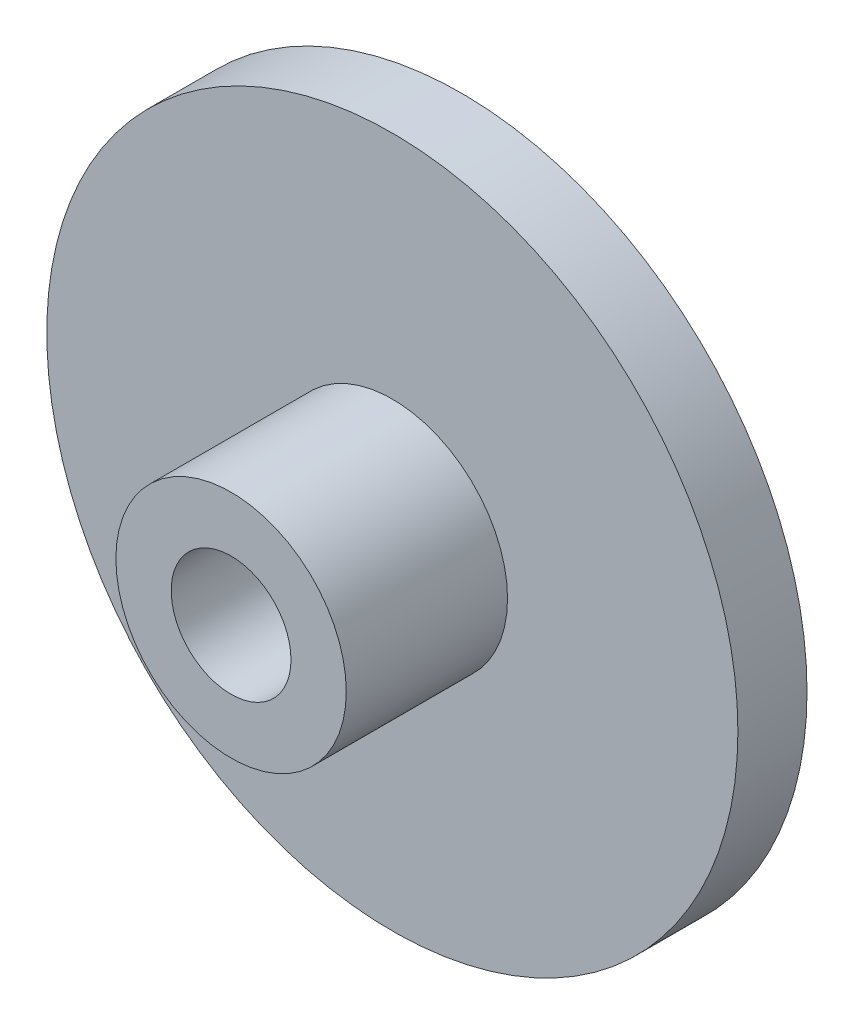
SolidWorks part; units mm, degrees
ref_plane "前视基准面" through (0, 0, 0) normal (0, 0, 1) x (1, 0, 0)
ref_plane "上视基准面" through (0, 0, 0) normal (0, 1, 0) x (1, 0, 0)
ref_plane "右视基准面" through (0, 0, 0) normal (1, 0, 0) x (0, 0, -1)
other "Configuration Table"
sketch "草图1" plane through (0, 0, 0) normal (0, 0, 1) x (1, 0, 0)
  circle A0 centre (0, 0) radius 15
  dimension "D1" = 30
extrude "凸台-拉伸1" add sketch "草图1" along normal blind 3
sketch "草图2" plane through (0, 0, 3) normal (0, 0, 1) x (1, 0, 0)
  circle A0 centre (0, 0) radius 2.6
  circle A1 centre (0, 0) radius 5
  dimension "D1" = 5.2
  dimension "D2" = 10
extrude "凸台-拉伸2" add sketch "草图2" along normal blind 7
